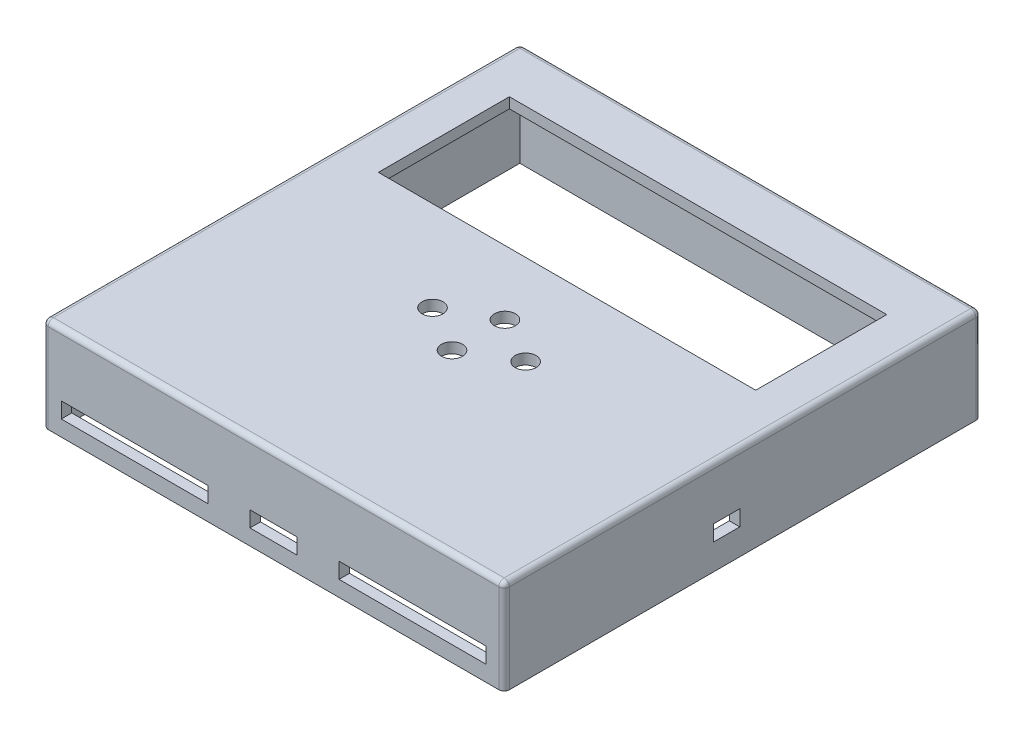
SolidWorks part; units mm, degrees
ref_plane "Front Plane" through (0, 0, 0) normal (0, 0, 1) x (1, 0, 0)
ref_plane "Top Plane" through (0, 0, 0) normal (0, 1, 0) x (1, 0, 0)
ref_plane "Right Plane" through (0, 0, 0) normal (1, 0, 0) x (0, 0, -1)
sketch "Sketch1" plane through (0, 0, 0) normal (0, 1, 0) x (1, 0, 0)
  line L1 (-49.7371, 49.101) -> (38.2629, 49.101)
  line L2 (-49.7371, 49.101) -> (-49.7371, -41.899)
  line L3 (-49.7371, -41.899) -> (38.2629, -41.899)
  line L4 (38.2629, 49.101) -> (38.2629, -41.899)
  dimension "D1" = 88
  dimension "D2" = 91
extrude "Boss-Extrude1" add sketch "Sketch1" along normal blind 18
shell "Shell1" thickness 2
fillet "Fillet1" radius 1 9 edges at (-49.7371, 9, -49.101) (-49.7371, 9, 41.899) (-49.7371, 0, -3.601) (-5.7371, 18, -49.101) (38.2629, 18, -3.601) (-5.7371, 18, 41.899) (-49.7371, 18, -3.601) (38.2629, 9, -49.101) (38.2629, 9, 41.899)
sketch "Sketch2" plane through (0, 18, 0) normal (0, 1, 0) x (1, 0, 0)
  line L0 (-49.7371, -40.899) -> (-49.7371, 48.101) construction
  line L1 (-41.7371, 39.101) -> (30.2629, 39.101)
  line L2 (-41.7371, 39.101) -> (-41.7371, 14.101)
  line L3 (-41.7371, 14.101) -> (30.2629, 14.101)
  line L4 (30.2629, 39.101) -> (30.2629, 14.101)
  line L5 (38.2629, 48.101) -> (38.2629, -40.899) construction
  line L6 (-48.7371, 49.101) -> (37.2629, 49.101) construction
  circle A0 centre (-5.3097, 1.8184) radius 2
  circle A1 centre (-5.3097, -8.2749) radius 2
  circle A2 centre (-14.1887, -3.1144) radius 2
  circle A3 centre (3.5694, -3.1144) radius 2
  dimension "D1" = 72
  dimension "D2" = 25
  dimension "D3" = 8
  dimension "D4" = 8
  dimension "D5" = 10
extrude "Cut-Extrude1" cut sketch "Sketch2" against normal blind 18
sketch "Sketch3" plane through (0, 0, 41.899) normal (0, 0, 1) x (1, 0, 0)
  line L0 (-49.7371, 1) -> (-49.7371, 17) construction
  line L1 (-46.2371, 5.9954) -> (-18.2371, 5.9954)
  line L2 (-46.2371, 5.9954) -> (-46.2371, 2.9954)
  line L3 (-46.2371, 2.9954) -> (-18.2371, 2.9954)
  line L4 (-18.2371, 5.9954) -> (-18.2371, 2.9954)
  line L5 (6.7629, 5.9954) -> (34.7629, 5.9954)
  line L6 (6.7629, 5.9954) -> (6.7629, 2.9954)
  line L7 (6.7629, 2.9954) -> (34.7629, 2.9954)
  line L8 (34.7629, 5.9954) -> (34.7629, 2.9954)
  line L9 (-10.2371, 5.9954) -> (-1.2371, 5.9954)
  line L10 (-10.2371, 5.9954) -> (-10.2371, 2.9954)
  line L11 (-10.2371, 2.9954) -> (-1.2371, 2.9954)
  line L12 (-1.2371, 5.9954) -> (-1.2371, 2.9954)
  line L13 (38.2629, 17) -> (38.2629, 0) construction
  dimension "D1" = 28
  dimension "D2" = 28
  dimension "D3" = 3
  dimension "D4" = 3
  dimension "D5" = 25
  dimension "D6" = 3.5
  dimension "D7" = 3.5
  dimension "D8" = 9
  dimension "D9" = 3
  dimension "D10" = 8
  dimension "D11" = 8
extrude "Cut-Extrude2" cut sketch "Sketch3" against normal up to next
sketch "Sketch4" plane through (38.2629, 0, 0) normal (1, 0, 0) x (0, 0, -1)
  line L1 (-1.9403, 7.9428) -> (3.0597, 7.9428)
  line L2 (-1.9403, 7.9428) -> (-1.9403, 4.9428)
  line L3 (-1.9403, 4.9428) -> (3.0597, 4.9428)
  line L4 (3.0597, 7.9428) -> (3.0597, 4.9428)
  dimension "D1" = 5
  dimension "D2" = 3
extrude "Cut-Extrude3" cut sketch "Sketch4" against normal up to next
